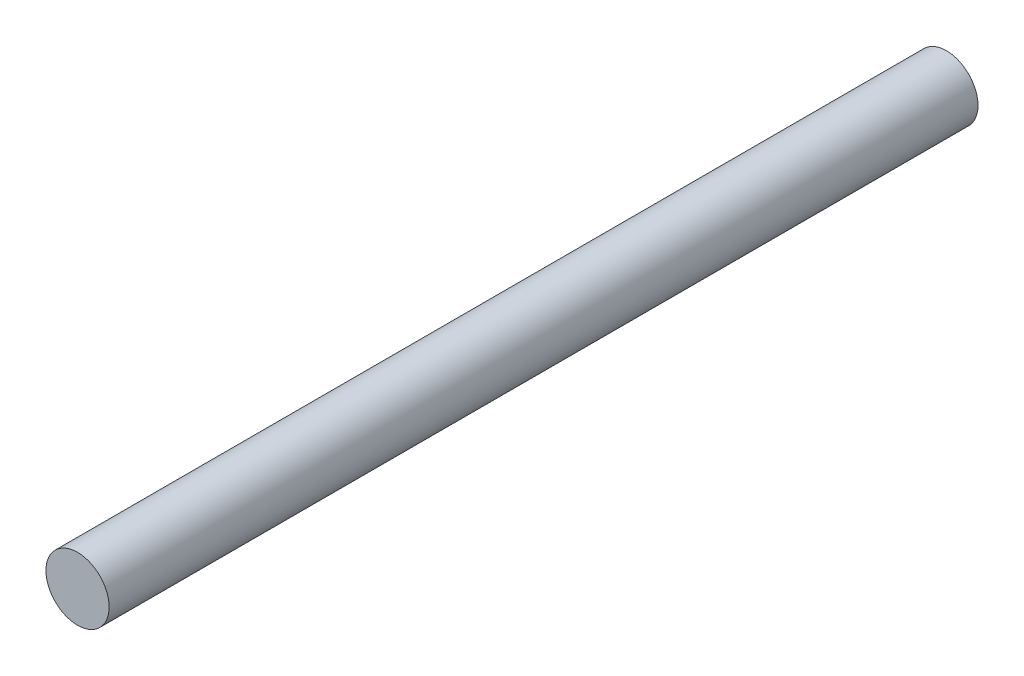
SolidWorks part; units mm, degrees
ref_plane "Plan de face" through (0, 0, 0) normal (0, 0, 1) x (1, 0, 0)
ref_plane "Plan de dessus" through (0, 0, 0) normal (0, 1, 0) x (1, 0, 0)
ref_plane "Plan de droite" through (0, 0, 0) normal (1, 0, 0) x (0, 0, -1)
sketch "Esquisse1" plane through (0, 0, 0) normal (0, 0, 1) x (1, 0, 0)
  circle A0 centre (0, 0) radius 0.6
  dimension "D1" = 1.2
extrude "Boss.-Extru.1" add sketch "Esquisse1" along normal blind 16.5
